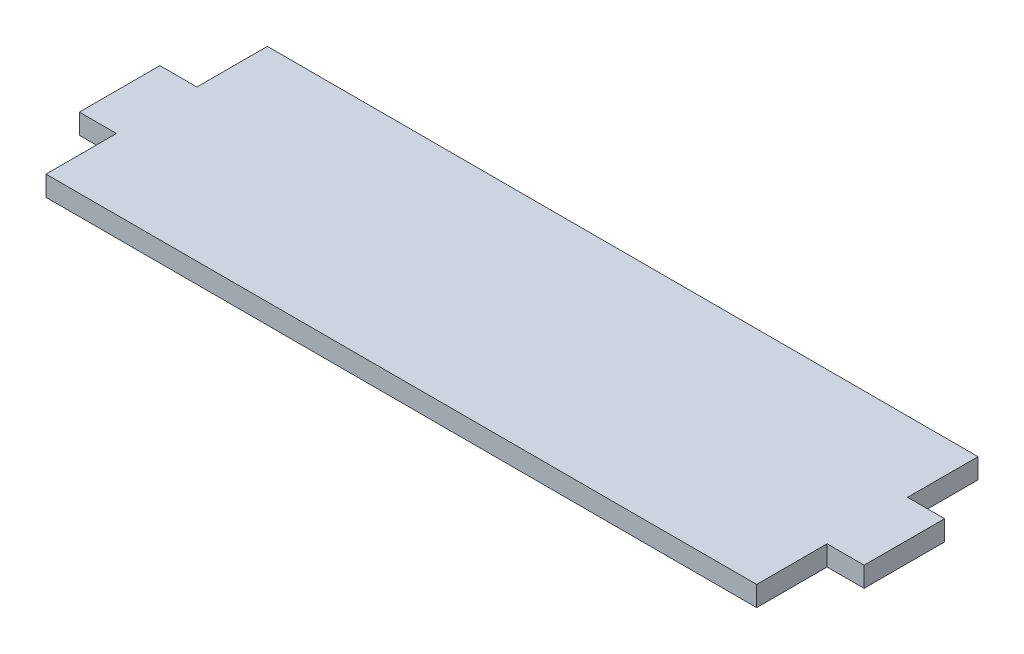
SolidWorks part; units mm, degrees
ref_plane "Front Plane" through (0, 0, 0) normal (0, 0, 1) x (1, 0, 0)
ref_plane "Top Plane" through (0, 0, 0) normal (0, 1, 0) x (1, 0, 0)
ref_plane "Right Plane" through (0, 0, 0) normal (1, 0, 0) x (0, 0, -1)
sketch "Sketch1" plane through (0, 0, 0) normal (0, 1, 0) x (1, 0, 0)
  line L0 (0, 17.4625) -> (0, -17.4625) construction
  line L1 (56.0705, -17.4625) -> (-56.0705, -17.4625)
  line L2 (56.0705, -17.4625) -> (56.0705, -6.35)
  line L3 (56.0705, 17.4625) -> (-56.0705, 17.4625)
  line L4 (-56.0705, -17.4625) -> (-56.0705, -6.35)
  line L5 (56.0705, -17.4625) -> (-56.0705, 17.4625) construction
  line L6 (56.0705, 17.4625) -> (-56.0705, -17.4625) construction
  line L7 (56.0705, 0) -> (-32.4683, 0) construction
  line L8 (-56.0705, 6.35) -> (-56.0705, 17.4625)
  line L9 (-61.9125, -6.35) -> (-56.0705, -6.35)
  line L10 (-61.9125, -6.35) -> (-61.9125, 6.35)
  line L11 (-61.9125, 6.35) -> (-56.0705, 6.35)
  line L12 (61.9125, 6.35) -> (56.0705, -6.35) construction
  line L13 (-61.9125, -6.35) -> (-56.0705, 6.35) construction
  line L14 (-61.9125, 6.35) -> (-56.0705, -6.35) construction
  line L15 (61.9125, -6.35) -> (56.0705, 6.35) construction
  line L16 (61.9125, 6.35) -> (56.0705, 6.35)
  line L17 (61.9125, -6.35) -> (61.9125, 6.35)
  line L18 (61.9125, -6.35) -> (56.0705, -6.35)
  line L19 (56.0705, 6.35) -> (56.0705, 17.4625)
  point P0 (0, 0)
  point P10 (-58.9915, 0)
  point P19 (58.9915, 0)
  dimension "D1" = 12.7
  dimension "D2" = 5.842
  dimension "D3" = 112.141
  dimension "D4" = 34.925
extrude "Boss-Extrude1" add sketch "Sketch1" along normal blind 3.175
